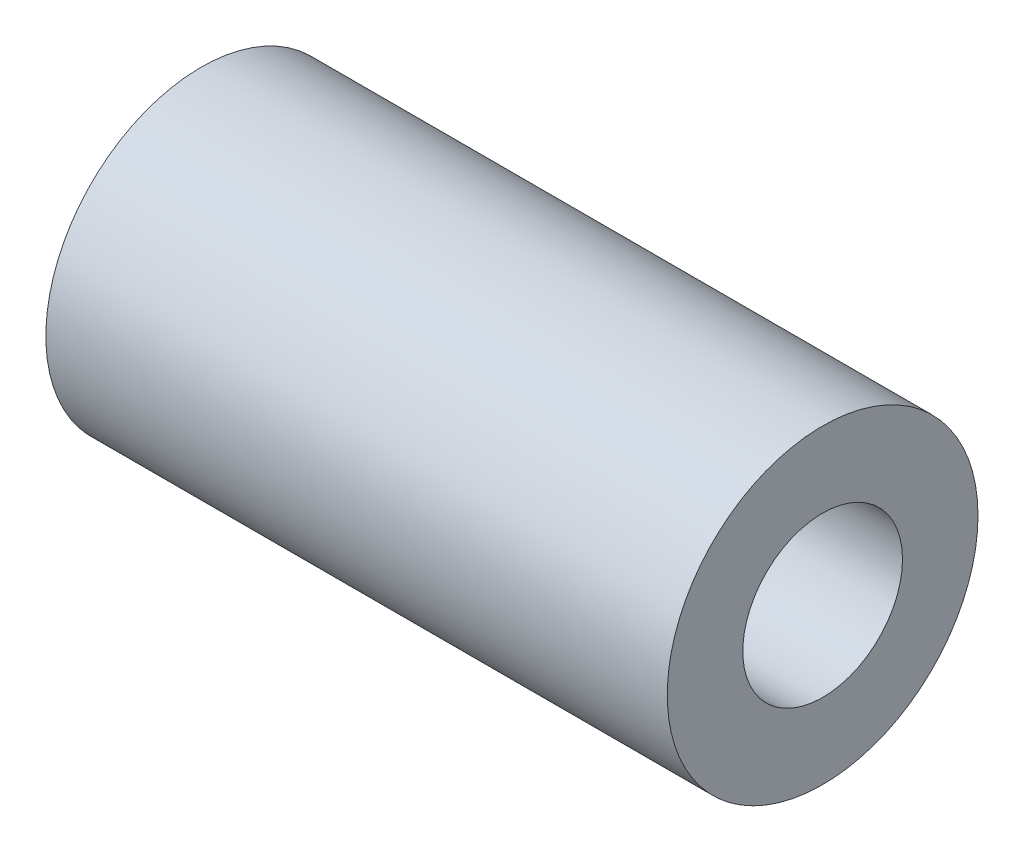
SolidWorks part; units mm, degrees
material "7075-T6 (SN)"
ref_plane "Front Plane" through (0, 0, 0) normal (0, 0, 1) x (1, 0, 0)
ref_plane "Top Plane" through (0, 0, 0) normal (0, 1, 0) x (1, 0, 0)
ref_plane "Right Plane" through (0, 0, 0) normal (1, 0, 0) x (0, 0, -1)
sketch "Sketch1" plane through (0, 0, 0) normal (1, 0, 0) x (0, 0, -1)
  circle A0 centre (0, 0) radius 3.2639
  circle A1 centre (0, 0) radius 6.35
  dimension "D1" = 12.7
  dimension "D2" = 6.5278
sketch "Sketch2" plane through (0, 0, 0) normal (1, 0, 0) x (0, 0, -1)
  circle A0 centre (0, 0) radius 3.2639 construction
  circle A1 centre (0, 0) radius 6.35 construction
  circle A2 centre (0, 0) radius 3.2639
  circle A3 centre (0, 0) radius 6.35
extrude "Boss-Extrude1" add sketch "Sketch2" along normal blind 25.4
